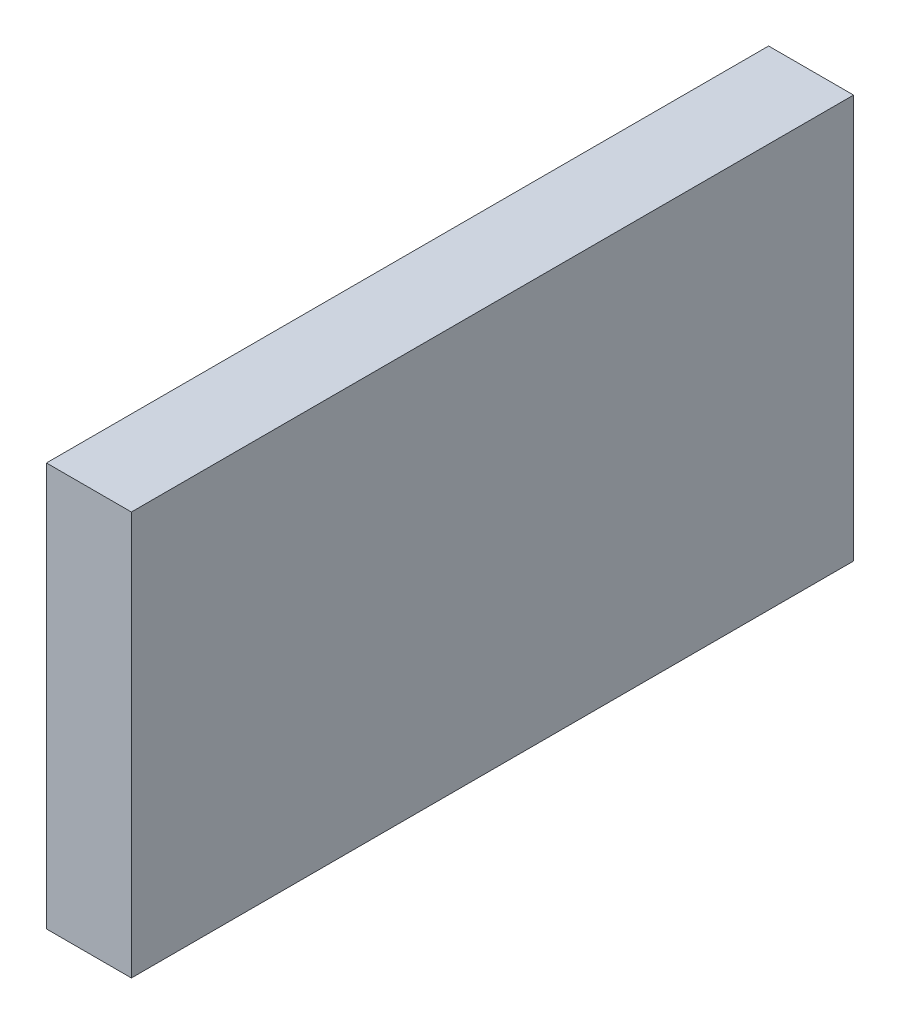
SolidWorks part; units mm, degrees
material "Glass"
ref_plane "Front Plane" through (0, 0, 0) normal (0, 0, 1) x (1, 0, 0)
ref_plane "Top Plane" through (0, 0, 0) normal (0, 1, 0) x (1, 0, 0)
ref_plane "Right Plane" through (0, 0, 0) normal (1, 0, 0) x (0, 0, -1)
sketch "Sketch1" plane through (0, 0, 0) normal (0, 0, 1) x (1, 0, 0)
  line L1 (0, 0) -> (101.6, 0)
  line L2 (0, 0) -> (0, 482.6)
  line L3 (0, 482.6) -> (101.6, 482.6)
  line L4 (101.6, 0) -> (101.6, 482.6)
  dimension "D1" = 482.6
  dimension "D2" = 101.6
extrude "Boss-Extrude1" add sketch "Sketch1" along normal blind 863.6
